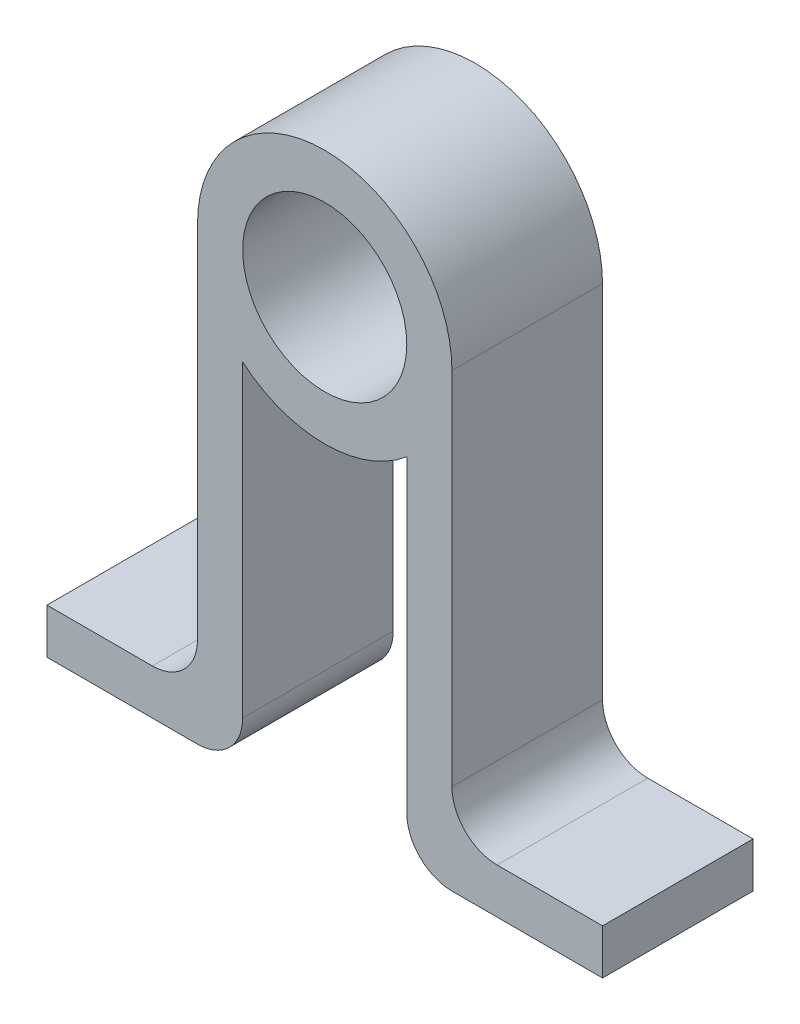
SolidWorks part; units mm, degrees
ref_plane "Front Plane" through (0, 0, 0) normal (0, 0, 1) x (1, 0, 0)
ref_plane "Top Plane" through (0, 0, 0) normal (0, 1, 0) x (1, 0, 0)
ref_plane "Right Plane" through (0, 0, 0) normal (1, 0, 0) x (0, 0, -1)
sketch "Sketch1" plane through (0, 0, 0) normal (0, 0, 1) x (1, 0, 0)
  line L0 (-8.45, 0) -> (-8.45, -23.94)
  line L1 (-11.45, -26.94) -> (-18.45, -26.94)
  line L2 (-18.45, -26.94) -> (-18.45, -29.94)
  line L3 (-18.45, -29.94) -> (-8.45, -29.94)
  line L4 (-5.45, -26.94) -> (-5.45, -6.4576)
  line L5 (0, 0) -> (0, -8.45) construction
  line L6 (5.45, -26.94) -> (5.45, -6.4576)
  line L7 (18.45, -29.94) -> (8.45, -29.94)
  line L8 (18.45, -26.94) -> (18.45, -29.94)
  line L9 (11.45, -26.94) -> (18.45, -26.94)
  line L10 (8.45, 0) -> (8.45, -23.94)
  circle A0 centre (0, 0) radius 5.45
  circle A1 centre (0, 0) radius 8.45
  arc A2 (-5.45, -26.94) -> (-8.45, -29.94) centre (-8.45, -26.94) cw
  arc A3 (-11.45, -26.94) -> (-8.45, -23.94) centre (-11.45, -23.94) ccw
  arc A4 (11.45, -26.94) -> (8.45, -23.94) centre (11.45, -23.94) cw
  arc A5 (5.45, -26.94) -> (8.45, -29.94) centre (8.45, -26.94) ccw
  dimension "D1" = 10.9
  dimension "D5" = 3
  dimension "D3" = 3
  dimension "D4" = 3
  dimension "D6" = 29.94
  dimension "D7" = 10
  dimension "D2" = 3
extrude "Boss-Extrude1" add sketch "Sketch1" along normal blind 10
